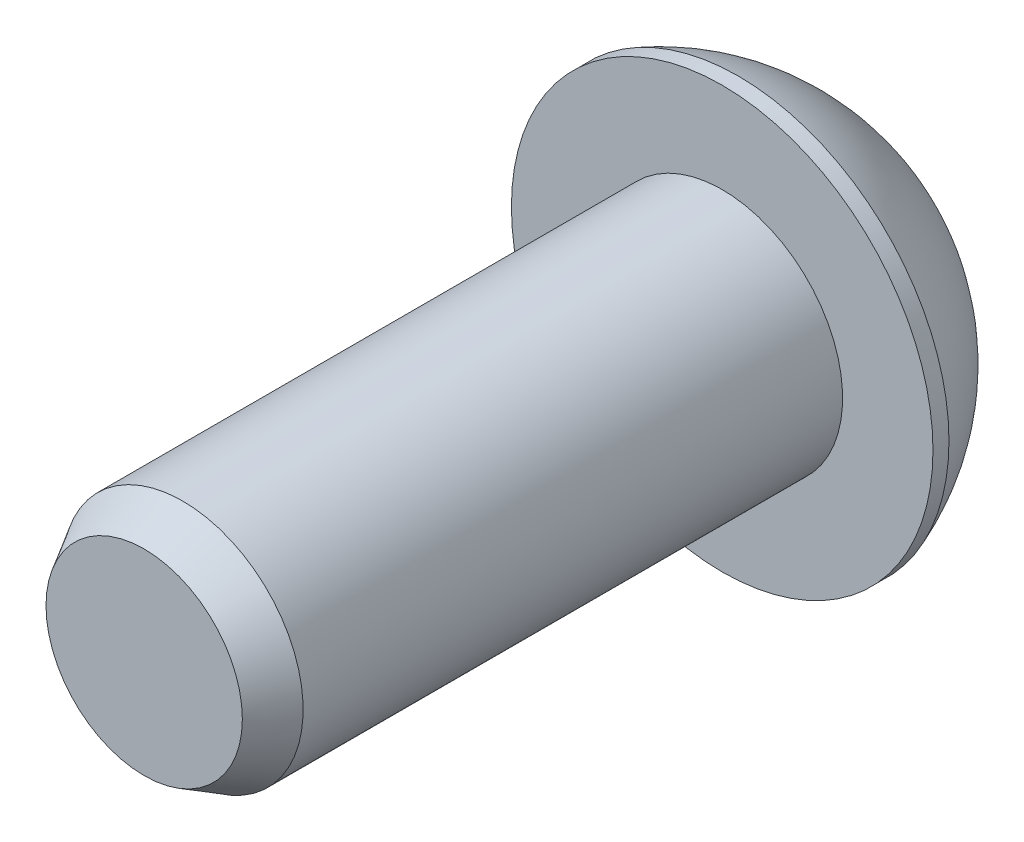
SolidWorks part; units mm, degrees
ref_plane "Front Plane" through (0, 0, 0) normal (0, 0, 1) x (1, 0, 0)
ref_plane "Top Plane" through (0, 0, 0) normal (0, 1, 0) x (1, 0, 0)
ref_plane "Right Plane" through (0, 0, 0) normal (1, 0, 0) x (0, 0, -1)
sketch "Sketch1" plane through (0, 0, 0) normal (0, 1, 0) x (1, 0, 0)
  line L0 (6.9469, -4.2164) -> (6.9469, -3.6893)
  line L1 (6.9469, -4.2164) -> (0, -4.2164)
  line L2 (0, 0) -> (3.9624, 0)
  line L3 (0, 0) -> (0, 0.6396) construction
  line L4 (0, -4.2164) -> (0, 0)
  arc A0 (6.9469, -3.6893) -> (3.9624, 0) centre (0, -6.2572) ccw
revolve "Revolve1" add sketch "Sketch1" angle 360 about L3
sketch "Sketch2" plane through (0, 0, 0) normal (0, 0, -1) x (-1, 0, 0)
  line L1 (2.7496, 0) -> (1.3748, 2.3813)
  line L2 (1.3748, 2.3813) -> (-1.3748, 2.3813)
  line L3 (-1.3748, 2.3813) -> (-2.7496, 0)
  line L4 (-2.7496, 0) -> (-1.3748, -2.3813)
  line L5 (-1.3748, -2.3813) -> (1.3748, -2.3813)
  line L6 (1.3748, -2.3813) -> (2.7496, 0)
  circle A0 centre (0, 0) radius 2.3813 construction
extrude "Cut-Extrude1" cut sketch "Sketch2" against normal blind 2.2225
sketch "Sketch3" plane through (0, 0, 4.2164) normal (0, 0, 1) x (1, 0, 0)
  circle A0 centre (0, 0) radius 3.9688
  dimension "D1" = 7.9375
extrude "Boss-Extrude1" add sketch "Sketch3" along normal blind 19.05
chamfer "Chamfer1" distance 1.27 angle 30 1 edges at (3.9688, 0, 23.2664)
